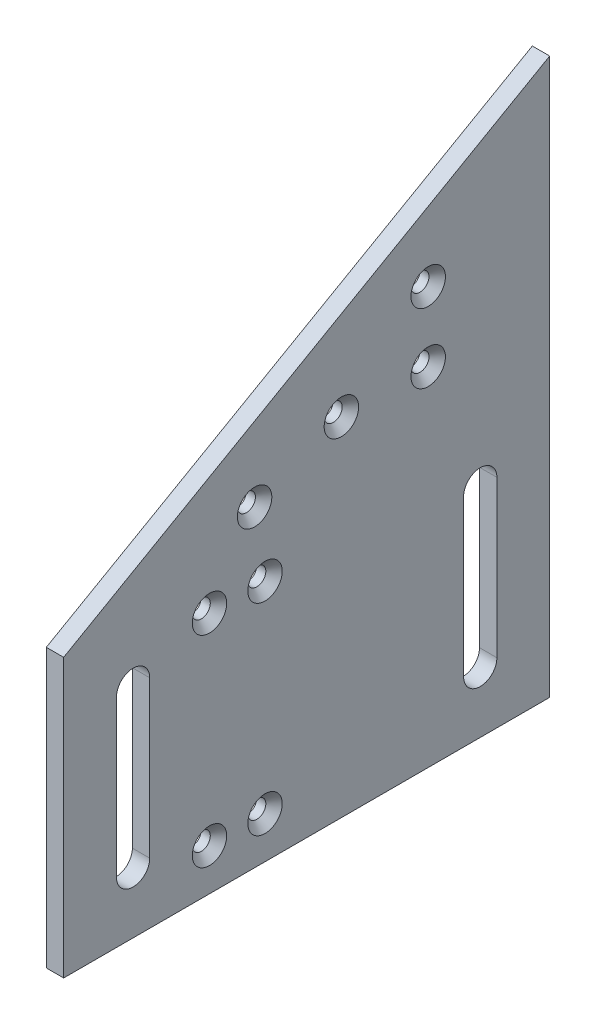
SolidWorks part; units mm, degrees
material "6061 Alloy"
ref_plane "Front Plane" through (0, 0, 0) normal (0, 0, 1) x (1, 0, 0)
ref_plane "Top Plane" through (0, 0, 0) normal (0, 1, 0) x (1, 0, 0)
ref_plane "Right Plane" through (0, 0, 0) normal (1, 0, 0) x (0, 0, -1)
sketch "Sketch2" plane through (0, 0, 0) normal (1, 0, 0) x (0, 0, -1)
  line L0 (-134.9156, 0) -> (-134.9156, 101.6)
  line L1 (55, 0) -> (-55, 0) construction
  line L2 (-134.9156, 101.6) -> (42.8844, 203.2)
  line L3 (42.8844, 203.2) -> (42.8844, 101.6)
  line L4 (42.8844, 101.6) -> (-134.9156, 101.6)
  line L5 (42.8844, 101.6) -> (42.8844, 0)
  line L6 (42.8844, 0) -> (-134.9156, 0)
  line L7 (42.8844, 0) -> (-134.9156, 0)
  line L8 (-109.5156, 22.225) -> (-109.5156, 79.375) construction
  line L9 (-115.5994, 22.225) -> (-115.5994, 79.375)
  line L10 (-103.4318, 22.225) -> (-103.4318, 79.375)
  line L11 (-46.0156, 0) -> (-46.0156, 101.6)
  line L12 (-46.0156, 50.8) -> (-109.5156, 50.8)
  line L13 (-46.0156, 50.8) -> (17.4844, 50.8)
  line L14 (17.4844, 22.225) -> (17.4844, 79.375) construction
  line L15 (23.5682, 22.225) -> (23.5682, 79.375)
  line L16 (11.4006, 22.225) -> (11.4006, 79.375)
  arc A0 (-115.5994, 22.225) -> (-103.4318, 22.225) centre (-109.5156, 22.225) ccw
  arc A1 (-103.4318, 79.375) -> (-115.5994, 79.375) centre (-109.5156, 79.375) ccw
  arc A2 (23.5682, 22.225) -> (11.4006, 22.225) centre (17.4844, 22.225) cw
  arc A3 (11.4006, 79.375) -> (23.5682, 79.375) centre (17.4844, 79.375) cw
  point P9 (-109.5156, 50.8)
  point P21 (17.4844, 50.8)
  dimension "D1" = 101.6
  dimension "D2" = 101.6
  dimension "D3" = 177.8
  dimension "D4" = 57.15
  dimension "D5" = 63.5
extrude "Boss-Extrude1" add sketch "Sketch2" along normal blind 6.35
sketch "Sketch4" plane through (6.35, 0, 0) normal (1, 0, 0) x (0, 0, -1)
  line L0 (-46.0156, 0) -> (-46.0156, 101.6)
  line L1 (3.4925, 0) -> (-3.4925, 0) construction
  line L2 (-134.9156, 101.6) -> (42.8844, 101.6)
  line L3 (42.8844, 203.2) -> (42.8844, 0) construction
  line L4 (-46.0156, 88.9) -> (-61.2556, 88.9)
  line L5 (-61.2556, 88.9) -> (-81.5756, 88.9)
  line L7 (-71.4156, 15.24) -> (-61.2556, 15.24)
  line L8 (-71.4156, 15.24) -> (-81.5756, 15.24)
  line L9 (-71.4156, 50.8) -> (-46.0156, 50.8)
  line L10 (-46.0156, 101.6) -> (-46.0156, 7.62)
  line L11 (-71.4156, 88.9) -> (-71.4156, 50.8)
  line L13 (-71.4156, 15.24) -> (-71.4156, 50.8)
  point P10 (-81.5756, 88.9)
  point P13 (-61.2556, 88.9)
  point P15 (-61.2556, 15.24)
  point P16 (-81.5756, 15.24)
  dimension "D1" = 7.62
  dimension "D2" = 12.7
  dimension "D3" = 10.16
  dimension "D4" = 20.32
  dimension "D5" = 93.98
  dimension "D6" = 25.4
hole_wizard "CSK for M6 Flat Head Machine Screw1" positions "Sketch4" profile "Sketch7" countersink size "M6" standard "ANSI Metric" end condition through all
sketch "Sketch7" plane through (6.35, 15.24, 81.5756) normal (0, 1, 0) x (0, 0, -1)
  line L0 (0, 0) -> (0, 6.35)
  line L1 (0, 6.35) -> (3.3, 6.35)
  line L2 (3.3, 6.35) -> (3.3, 3)
  line L3 (3.3, 3) -> (6.3, 0)
  line L5 (6.3, 0) -> (0, 0)
  line L6 (-3.3, 3) -> (-6.3, 0) construction
  line L11 (0, -6.35) -> (0, 107.95) construction
  dimension "Thru Hole Dia." = 6.6
  dimension "Thru Hole Depth" = 6.35
  dimension "Near C'Sink Dia." = 12.6
  dimension "Near C'Sink Angle" = 90
sketch "Sketch8" plane through (6.35, 0, 0) normal (1, 0, 0) x (0, 0, -1)
  line L0 (-134.9156, 101.6) -> (42.8844, 101.6)
  line L1 (42.8844, 203.2) -> (42.8844, 0) construction
  line L2 (42.8844, 101.6) -> (-33.3156, 101.6)
  line L3 (-33.3156, 101.6) -> (-33.3156, 127)
  line L4 (-33.3156, 127) -> (-1.5656, 127)
  line L5 (-1.5656, 127) -> (-1.5656, 152.4)
  line L6 (-1.5656, 127) -> (-1.5656, 101.6)
  line L7 (-33.3156, 127) -> (-65.0656, 127)
  line L8 (-65.0656, 127) -> (-65.0656, 101.6)
  point P7 (-33.3156, 127)
  point P8 (-1.5656, 127)
  point P9 (-1.5656, 152.4)
  point P13 (-65.0656, 114.3)
  dimension "D1" = 76.2
  dimension "D2" = 31.75
  dimension "D3" = 31.75
  dimension "D4" = 25.4
  dimension "D5" = 50.8
hole_wizard "CSK for M6 Flat Head Machine Screw2" positions "Sketch8" profile "Sketch9" countersink size "M6" standard "ANSI Metric" end condition through all
sketch "Sketch9" plane through (6.35, 114.3, 65.0656) normal (0, 1, 0) x (0, 0, -1)
  line L0 (0, 0) -> (0, 6.35)
  line L1 (0, 6.35) -> (3.3, 6.35)
  line L2 (3.3, 6.35) -> (3.3, 3)
  line L3 (3.3, 3) -> (6.3, 0)
  line L5 (6.3, 0) -> (0, 0)
  line L6 (-3.3, 3) -> (-6.3, 0) construction
  line L11 (0, -6.35) -> (0, 107.95) construction
  dimension "Thru Hole Dia." = 6.6
  dimension "Thru Hole Depth" = 6.35
  dimension "Near C'Sink Dia." = 12.6
  dimension "Near C'Sink Angle" = 90
equation "\"plateheight\"= 3.5in"
equation "\"platethickness\"= 0.5in"
equation "\"brakedplatethickness\"= 0.25in"
equation "\"backplateheight\"= 4.125in"
equation "\"axlemounttolerance\"= 0.1in"
equation "\"brakedplatetolerance\"= 0.03in"
equation "\"beltholethickness\"= 0.3in"
equation "\"beltholeheight\"= 2in"
equation "\"waistcentertohipoffsetaverage\"= 1in'posterior distance of center of axle mount from center of plate"
equation "\"screwholeheightoffset\"= 0.3in'difference between upper/lower faces of flat plate and the screw holes for the axle mount"
equation "\"platedepth\"= 7in'take smallest waist depth 7.4in and subtract 0.4in"
equation "\"brakedplatematethickness\"= 0.25in'diffrence from both edges to braked plate"
equation "\"brakedplateholemargin\"= 0.5in'extra vertical bit to transition between plate and braked plate mount"
equation "\"rodmountwidth\"= 1.5in"
equation "\"screwholewidthoffset\"= 0.35in"
